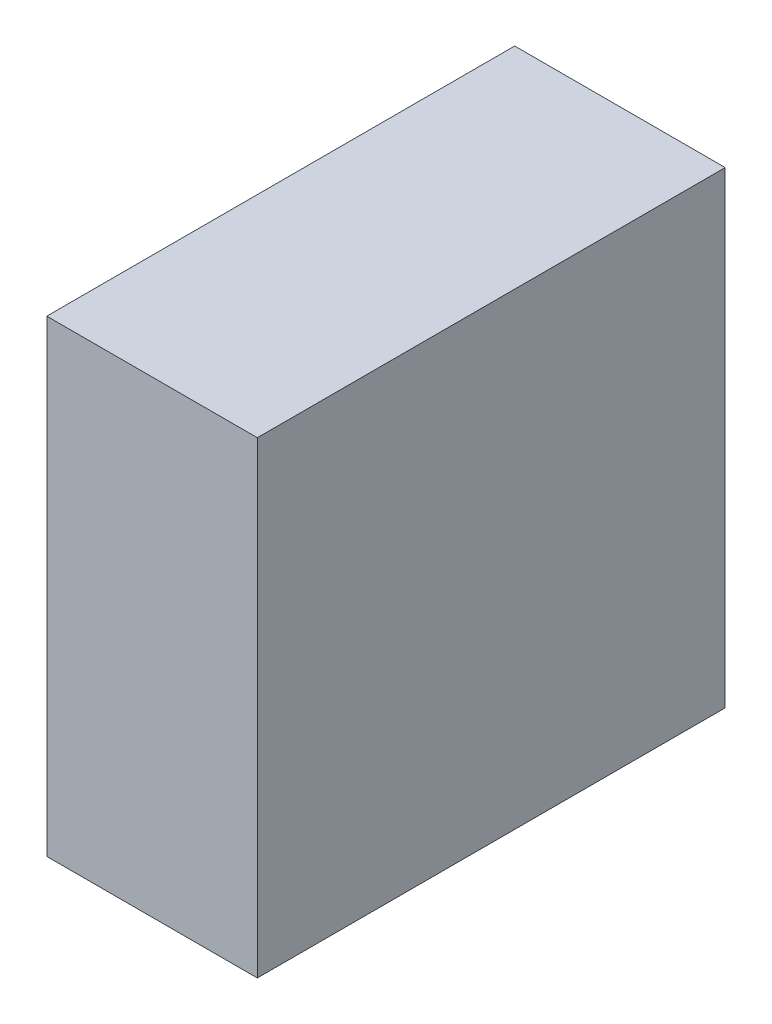
SolidWorks part; units mm, degrees
ref_plane "Front Plane" through (0, 0, 0) normal (0, 0, 1) x (1, 0, 0)
ref_plane "Top Plane" through (0, 0, 0) normal (0, 1, 0) x (1, 0, 0)
ref_plane "Right Plane" through (0, 0, 0) normal (1, 0, 0) x (0, 0, -1)
other "Configuration Table"
sketch "Sketch1" plane through (0, 0, 0) normal (0, 0, 1) x (1, 0, 0)
  line L1 (390, 180) -> (435, 180)
  line L2 (390, 180) -> (390, 280)
  line L3 (390, 280) -> (435, 280)
  line L4 (435, 180) -> (435, 280)
extrude "PACK_pano_motor_surucu_1_1" add sketch "Sketch1" against normal blind 100 from offset 148 separate body
